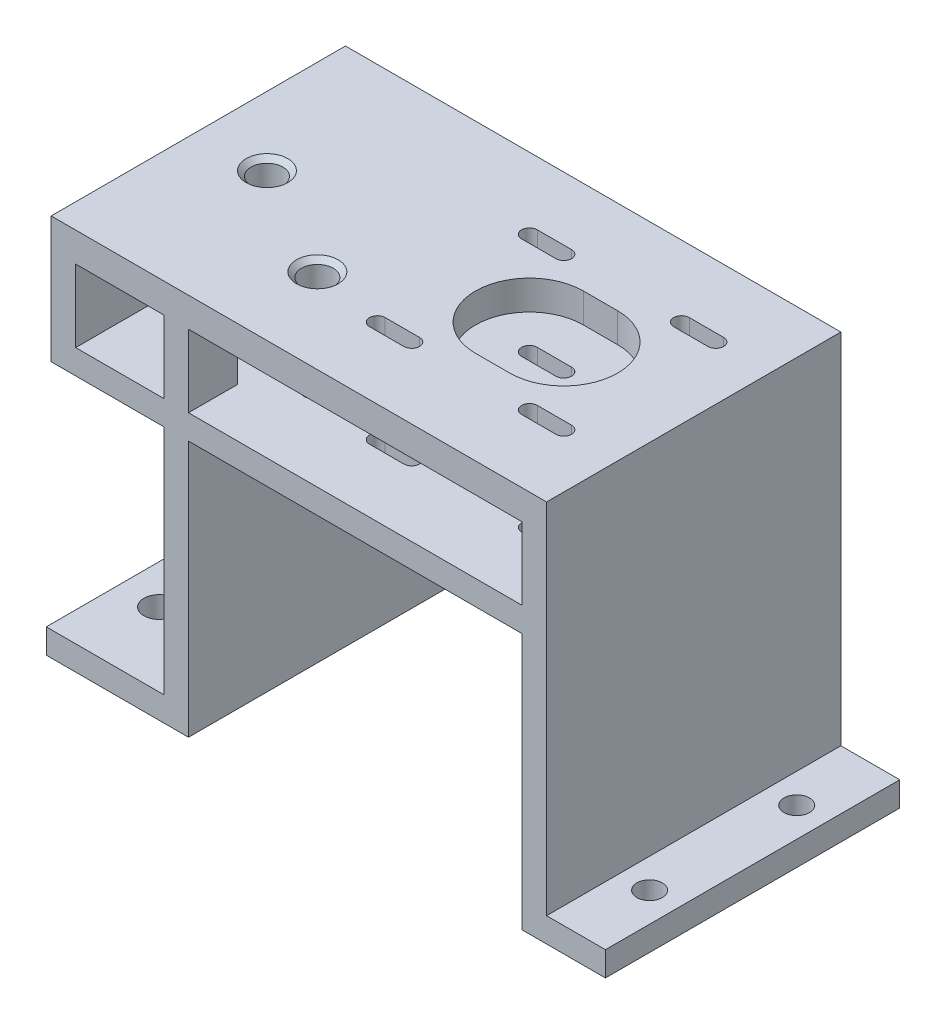
SolidWorks part; units mm, degrees
material "PET"
ref_plane "Front Plane" through (0, 0, 0) normal (0, 0, 1) x (1, 0, 0)
ref_plane "Top Plane" through (0, 0, 0) normal (0, 1, 0) x (1, 0, 0)
ref_plane "Right Plane" through (0, 0, 0) normal (1, 0, 0) x (0, 0, -1)
sketch "Sketch1" plane through (0, 0, 0) normal (0, 0, 1) x (1, 0, 0)
  line L0 (0, 0) -> (-29, 0)
  line L1 (-29, 0) -> (-29, 5)
  line L2 (-29, 5) -> (-5, 5)
  line L3 (-5, 5) -> (-5, 52.3)
  line L6 (-28, 78.05) -> (73, 78.05)
  line L7 (73, 78.05) -> (73, 5)
  line L10 (85, 0) -> (68, 0)
  line L11 (68, 0) -> (68, 52.3)
  line L12 (68, 72.05) -> (0, 72.05)
  line L13 (0, 72.05) -> (0, 57.3)
  line L14 (0, 57.3) -> (68, 57.3)
  line L16 (68, 52.3) -> (0, 52.3)
  line L17 (0, 0) -> (0, 52.3)
  line L19 (-28, 78.05) -> (-28, 52.3)
  line L20 (-28, 52.3) -> (-5, 52.3)
  line L21 (-5, 72.05) -> (-23, 72.05)
  line L22 (-23, 72.05) -> (-23, 57.3)
  line L23 (-23, 57.3) -> (-5, 57.3)
  line L25 (-5, 57.3) -> (-5, 72.05)
  line L28 (68, 57.3) -> (68, 72.05)
  line L29 (73, 5) -> (85, 5)
  line L30 (85, 5) -> (85, 0)
  point P19 (0, 26.15)
  point P28 (-29, 2.5)
  dimension "D1" = 5
  dimension "D2" = 6
  dimension "D3" = 5
  dimension "D4" = 5
  dimension "D5" = 5
  dimension "D6" = 14.75
  dimension "D7" = 57.3
  dimension "D8" = 101
  dimension "D9" = 5
  dimension "D10" = 12
  dimension "D13" = 23
  dimension "D14" = 5
  dimension "D15" = 5
  dimension "D16" = 24
extrude "Boss-Extrude1" add sketch "Sketch1" along normal blind 60
sketch "Sketch2" plane through (0, 0, 0) normal (1, 0, 0) x (0, 0, -1)
  line L0 (-60, 5) -> (-60, 78.05) construction
  line L1 (-50, 72.05) -> (-10, 72.05)
  line L2 (-50, 72.05) -> (-50, 57.3)
  line L3 (-50, 57.3) -> (-10, 57.3)
  line L4 (-10, 72.05) -> (-10, 57.3)
  line L5 (-60, 78.05) -> (0, 78.05) construction
  line L6 (0, 5) -> (0, 78.05) construction
  dimension "D1" = 10
  dimension "D2" = 14.75
  dimension "D3" = 6
  dimension "D4" = 10
extrude "Cut-Extrude1" cut sketch "Sketch2" against normal up to next
sketch "Sketch3" plane through (0, 78.05, 0) normal (0, 1, 0) x (1, 0, 0)
  line L0 (18, -30) -> (68, -30) construction
  line L2 (73, -60) -> (73, 0) construction
  line L3 (39.5, -30) -> (46.5, -30) construction
  line L4 (39.5, -19) -> (46.5, -19)
  line L5 (39.5, -41) -> (46.5, -41)
  line L6 (31, -14.5) -> (24, -14.5) construction
  line L7 (31, -16.1) -> (24, -16.1)
  line L8 (31, -12.9) -> (24, -12.9)
  line L9 (43, -30) -> (43, 0) construction
  line L10 (73, -60) -> (-28, -60) construction
  line L12 (73, 0) -> (-28, 0) construction
  line L13 (55, -14.5) -> (62, -14.5) construction
  line L14 (55, -16.1) -> (62, -16.1)
  line L15 (55, -12.9) -> (62, -12.9)
  line L16 (31, -45.5) -> (24, -45.5) construction
  line L17 (31, -43.9) -> (24, -43.9)
  line L18 (31, -47.1) -> (24, -47.1)
  line L19 (55, -45.5) -> (62, -45.5) construction
  line L20 (55, -43.9) -> (62, -43.9)
  line L21 (55, -47.1) -> (62, -47.1)
  arc A0 (39.5, -19) -> (39.5, -41) centre (39.5, -30) ccw
  arc A1 (46.5, -41) -> (46.5, -19) centre (46.5, -30) ccw
  arc A2 (31, -16.1) -> (31, -12.9) centre (31, -14.5) ccw
  arc A3 (24, -12.9) -> (24, -16.1) centre (24, -14.5) ccw
  arc A4 (55, -16.1) -> (55, -12.9) centre (55, -14.5) cw
  arc A5 (62, -12.9) -> (62, -16.1) centre (62, -14.5) cw
  arc A6 (31, -43.9) -> (31, -47.1) centre (31, -45.5) cw
  arc A7 (24, -47.1) -> (24, -43.9) centre (24, -45.5) cw
  arc A8 (55, -43.9) -> (55, -47.1) centre (55, -45.5) ccw
  arc A9 (62, -47.1) -> (62, -43.9) centre (62, -45.5) ccw
  point P8 (43, -30)
  point P15 (27.5, -14.5)
  point P24 (58.5, -14.5)
  point P31 (27.5, -45.5)
  point P38 (58.5, -45.5)
  dimension "D2" = 11
  dimension "D4" = 1.6
  dimension "D1" = 7
  dimension "D3" = 7
  dimension "D5" = 15.5
  dimension "D6" = 15.5
  dimension "D7" = 5
  dimension "D8" = 55
  dimension "D9" = 30
extrude "Cut-Extrude2" cut sketch "Sketch3" against normal through all
sketch "Sketch5" plane through (0, 78.05, 0) normal (0, 1, 0) x (1, 0, 0)
  line L0 (73, -30) -> (-28, -30) construction
  line L4 (73, -60) -> (73, 0) construction
  line L5 (-28, -60) -> (-28, 0) construction
  circle A0 centre (9, -42.73) radius 3.25
  dimension "D1" = 6.5
  dimension "D3" = 64
  dimension "D2" = 12.73
extrude "Cut-Extrude3" cut sketch "Sketch5" against normal up to next
sketch "Sketch6" plane through (0, 57.3, 0) normal (0, 1, 0) x (1, 0, 0)
  circle A0 centre (9, -42.73) radius 2.6
  dimension "D1" = 5.2
extrude "Cut-Extrude4" cut sketch "Sketch6" against normal up to next
sketch "Sketch7" plane through (0, 78.05, 0) normal (0, 1, 0) x (1, 0, 0)
  line L0 (28.5, -30) -> (-29, -30) construction
  line L3 (-29, -60) -> (-29, 0) construction
  line L4 (-28, -60) -> (-28, 0) construction
  arc A0 (39.5, -19) -> (39.5, -41) centre (39.5, -30) ccw construction
  circle A1 centre (-14, -30) radius 2.6
  dimension "D1" = 14
  dimension "D2" = 5.2
extrude "Cut-Extrude5" cut sketch "Sketch7" against normal through all
sketch "Sketch8" plane through (0, 78.05, 0) normal (0, 1, 0) x (1, 0, 0)
  circle A0 centre (-14, -30) radius 3.25
  dimension "D1" = 6.5
extrude "Cut-Extrude6" cut sketch "Sketch8" against normal up to next
chamfer "Chamfer1" distance 1 angle 45 2 edges at (-14, 78.05, 33.25) (9, 78.05, 45.98)
ref_plane "Plane1" through (9, 0, 0) normal (1, 0, 0) x (0, 0, -1)
sketch "Sketch10" plane through (0, 0, 0) normal (0, -1, 0) x (1, 0, 0)
  line L0 (-21, 60) -> (-21, 0) construction
  line L1 (-29, 60) -> (0, 60) construction
  line L2 (-29, 0) -> (0, 0) construction
  line L3 (79, 60) -> (79, 0) construction
  line L4 (68, 60) -> (85, 60) construction
  line L5 (68, 0) -> (85, 0) construction
  line L6 (0, 60) -> (0, 0) construction
  line L7 (-21, 45) -> (79, 45) construction
  line L8 (-29, 30) -> (73, 30) construction
  line L9 (-29, 60) -> (-29, 0) construction
  line L10 (85, 60) -> (85, 0) construction
  line L11 (-21, 15) -> (79, 15) construction
  line L12 (73, 60) -> (73, 0) construction
  circle A0 centre (-21, 45) radius 3.1
  circle A1 centre (-21, 15) radius 3.1
  circle A2 centre (79, 15) radius 2.6
  circle A3 centre (79, 45) radius 2.6
  dimension "D5" = 6.2
  dimension "D6" = 6.2
  dimension "D7" = 5.2
  dimension "D8" = 5.2
  dimension "D1" = 21
  dimension "D2" = 15
  dimension "D3" = 15
  dimension "D4" = 6
extrude "Cut-Extrude8" cut sketch "Sketch10" against normal up to next
sketch "Sketch11" plane through (0, 52.3, 0) normal (0, -1, 0) x (1, 0, 0)
  line L0 (0, 60) -> (0, 0) construction
  line L1 (0, 38) -> (18.5, 38)
  line L2 (0, 38) -> (0, 22)
  line L3 (0, 22) -> (18.5, 22)
  line L4 (18.5, 38) -> (18.5, 22)
  line L5 (73, 30) -> (-28, 30) construction
  dimension "D1" = 5.5
  dimension "D2" = 8
  dimension "D3" = 16
extrude "Boss-Extrude2" add sketch "Sketch11" along normal blind 12
sketch "Sketch12" plane through (18.5, 0, 0) normal (1, 0, 0) x (0, 0, -1)
  line L0 (-38, 40.3) -> (-22, 52.3) construction
  circle A0 centre (-29.454, 46.7095) radius 3.25
  dimension "D1" = 6.5
extrude "Cut-Extrude9" cut sketch "Sketch12" against normal through all
chamfer "Chamfer2" distance 1 angle 45 1 edges at (-5, 49.9595, 29.454)
